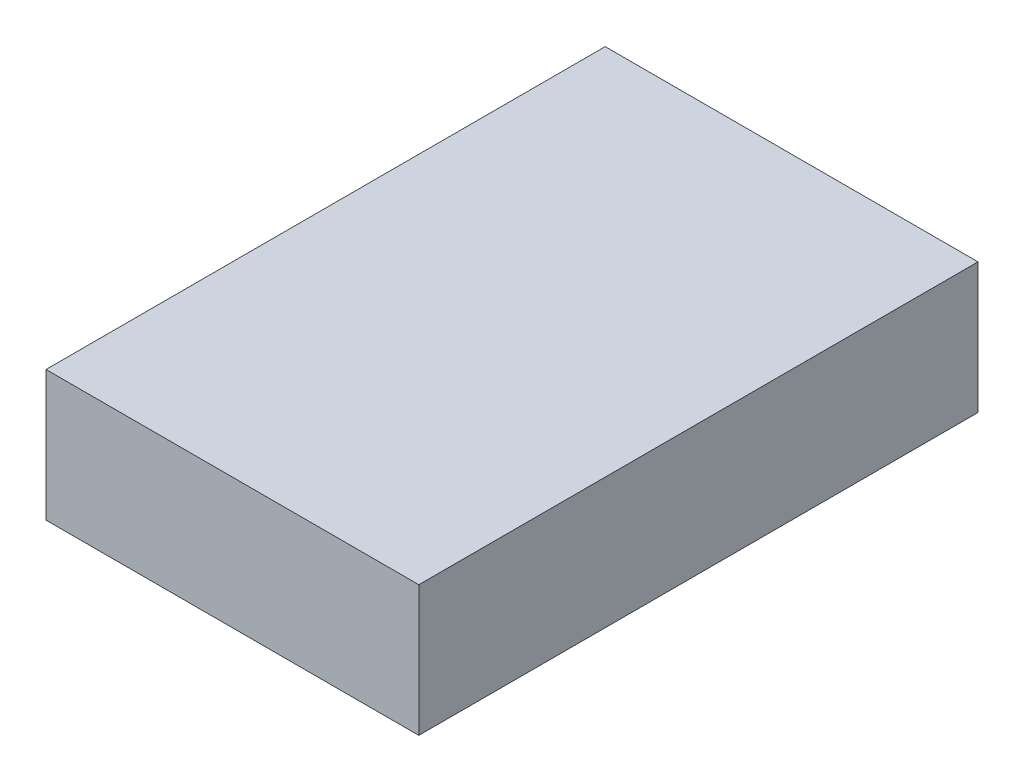
SolidWorks part; units mm, degrees
ref_plane "Front Plane" through (0, 0, 0) normal (0, 0, 1) x (1, 0, 0)
ref_plane "Top Plane" through (0, 0, 0) normal (0, 1, 0) x (1, 0, 0)
ref_plane "Right Plane" through (0, 0, 0) normal (1, 0, 0) x (0, 0, -1)
sketch "Sketch1" plane through (0, 0, 0) normal (0, 0, 1) x (1, 0, 0)
  line L0 (0, 0) -> (0, 640) construction
  line L2 (0, 0) -> (200, 0)
  line L3 (0, 0) -> (0, 70)
  line L4 (0, 70) -> (200, 70)
  line L5 (200, 0) -> (200, 70)
  dimension "D1" = 640
  dimension "D2" = 70
  dimension "D3" = 200
extrude "Boss-Extrude1" add sketch "Sketch1" along normal blind 300
